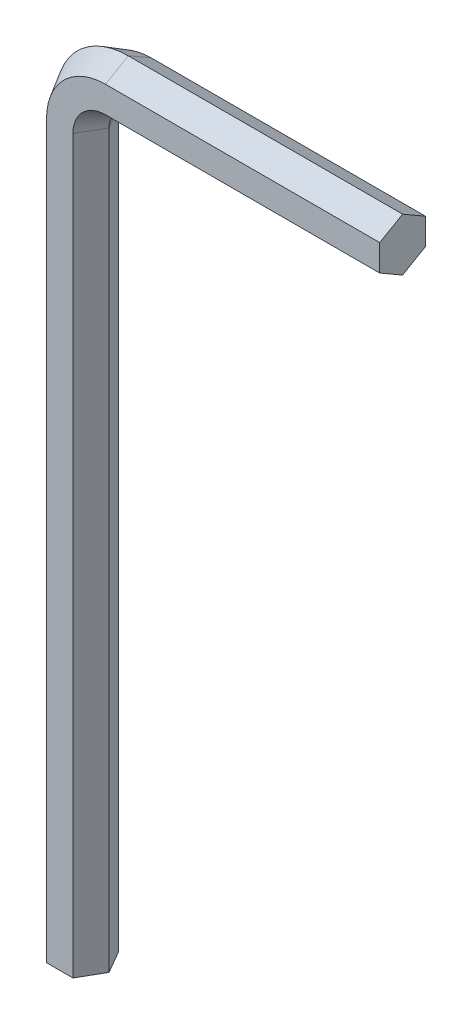
SolidWorks part; units mm, degrees
material "Stainless Steel (ferritic)"
ref_plane "Front Plane" through (0, 0, 0) normal (0, 0, 1) x (1, 0, 0)
ref_plane "Top Plane" through (0, 0, 0) normal (0, 1, 0) x (1, 0, 0)
ref_plane "Right Plane" through (0, 0, 0) normal (1, 0, 0) x (0, 0, -1)
sketch "Sketch1" plane through (0, 0, 0) normal (1, 0, 0) x (0, 0, -1)
  line L0 (0, 0) -> (0, -1.8331) construction
  line L1 (1.5875, 0.9165) -> (0, 1.8331)
  line L2 (0, 1.8331) -> (-1.5875, 0.9165)
  line L3 (-1.5875, 0.9165) -> (-1.5875, -0.9165)
  line L4 (-1.5875, -0.9165) -> (0, -1.8331)
  line L5 (0, -1.8331) -> (1.5875, -0.9165)
  line L6 (1.5875, -0.9165) -> (1.5875, 0.9165)
  circle A0 centre (0, 0) radius 1.5875 construction
  dimension "D1" = 3.175
extrude "Boss-Extrude1" add sketch "Sketch1" against normal blind 19.05
sketch "Sketch3" plane through (-19.05, 0, 0) normal (-1, 0, 0) x (0, 0, 1)
  line L0 (0, 0) -> (0, -3.175) construction
  line L1 (0, -3.175) -> (2.811, -3.175) construction
  line L6 (-1.5875, 0.9165) -> (-1.5875, -0.9165)
  line L7 (-1.5875, -0.9165) -> (0, -1.8331)
  line L8 (0, -1.8331) -> (1.5875, -0.9165)
  line L9 (1.5875, -0.9165) -> (1.5875, 0.9165)
  line L10 (1.5875, 0.9165) -> (0, 1.8331)
  line L11 (0, 1.8331) -> (-1.5875, 0.9165)
  line L12 (-1.5875, 0.9165) -> (-1.5875, -0.9165)
  line L13 (-1.5875, -0.9165) -> (0, -1.8331)
  line L14 (0, -1.8331) -> (1.5875, -0.9165)
  line L15 (1.5875, -0.9165) -> (1.5875, 0.9165)
  line L16 (1.5875, 0.9165) -> (0, 1.8331)
  line L17 (0, 1.8331) -> (-1.5875, 0.9165)
  dimension "D2" = 3.175
  dimension "D1" = 0
revolve "Revolve4" add sketch "Sketch3" angle 90 about L1
sketch "Sketch4" plane through (0, -3.175, 0) normal (0, -1, 0) x (1, 0, 0)
  line L6 (-24.0581, 0) -> (-23.1415, -1.5875)
  line L7 (-23.1415, -1.5875) -> (-21.3085, -1.5875)
  line L8 (-21.3085, -1.5875) -> (-20.3919, 0)
  line L9 (-20.3919, 0) -> (-21.3085, 1.5875)
  line L10 (-21.3085, 1.5875) -> (-23.1415, 1.5875)
  line L11 (-23.1415, 1.5875) -> (-24.0581, 0)
  line L12 (-24.0581, 0) -> (-23.1415, -1.5875)
  line L13 (-23.1415, -1.5875) -> (-21.3085, -1.5875)
  line L14 (-21.3085, -1.5875) -> (-20.3919, 0)
  line L15 (-20.3919, 0) -> (-21.3085, 1.5875)
  line L16 (-21.3085, 1.5875) -> (-23.1415, 1.5875)
  line L17 (-23.1415, 1.5875) -> (-24.0581, 0)
  dimension "D1" = 0
extrude "Boss-Extrude2" add sketch "Sketch4" along normal blind 50.8
